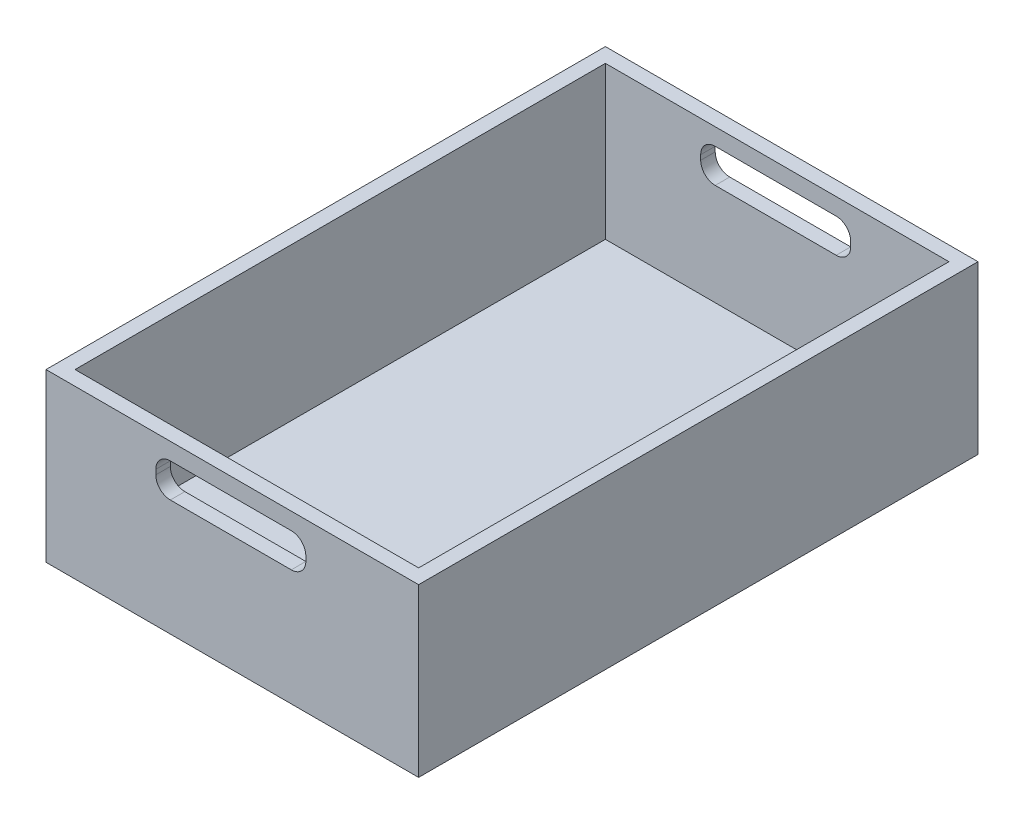
SolidWorks part; units mm, degrees
ref_plane "Front Plane" through (0, 0, 0) normal (0, 0, 1) x (1, 0, 0)
ref_plane "Top Plane" through (0, 0, 0) normal (0, 1, 0) x (1, 0, 0)
ref_plane "Right Plane" through (0, 0, 0) normal (1, 0, 0) x (0, 0, -1)
sketch "Sketch1" plane through (0, 0, 0) normal (0, 1, 0) x (1, 0, 0)
  line L1 (-192.5, -289) -> (192.5, -289)
  line L2 (-192.5, -289) -> (-192.5, 289)
  line L3 (-192.5, 289) -> (192.5, 289)
  line L4 (192.5, -289) -> (192.5, 289)
  line L5 (-192.5, -289) -> (192.5, 289) construction
  line L6 (-192.5, 289) -> (192.5, -289) construction
  point P0 (0, 0)
  dimension "D1" = 385
  dimension "D2" = 578
extrude "Boss-Extrude1" add sketch "Sketch1" along normal blind 15
sketch "Sketch2" plane through (0, 15, 0) normal (0, 1, 0) x (1, 0, 0)
  line L0 (192.5, 289) -> (-192.5, 289) construction
  line L1 (192.5, -289) -> (177.5, -289)
  line L2 (192.5, -289) -> (192.5, 289)
  line L3 (192.5, 289) -> (177.5, 289)
  line L4 (177.5, -289) -> (177.5, 289)
  dimension "D1" = 15
extrude "Boss-Extrude2" add sketch "Sketch2" along normal blind 157.5
mirror "Mirror1" about plane through (0, 0, 0) normal (1, 0, 0) of "Boss-Extrude2"
sketch "Sketch3" plane through (0, 15, 0) normal (0, 1, 0) x (1, 0, 0)
  line L0 (177.5, 289) -> (177.5, -289) construction
  line L1 (-177.5, -289) -> (177.5, -289)
  line L2 (-177.5, -289) -> (-177.5, -274)
  line L3 (-177.5, -274) -> (177.5, -274)
  line L4 (177.5, -289) -> (177.5, -274)
  dimension "D1" = 15
extrude "Boss-Extrude3" add sketch "Sketch3" along normal blind 157.5
mirror "Mirror2" about plane through (0, 0, 0) normal (0, 0, 1) of "Boss-Extrude3"
sketch "Sketch4" plane through (0, 0, 289) normal (0, 0, 1) x (1, 0, 0)
  line L1 (-64.0344, 155) -> (60.9656, 155)
  line L2 (-79.0344, 140) -> (-79.0344, 135)
  line L3 (-64.0344, 120) -> (60.9656, 120)
  line L4 (75.9656, 140) -> (75.9656, 135)
  line L5 (-79.0344, 155) -> (75.9656, 120) construction
  line L6 (-79.0344, 120) -> (75.9656, 155) construction
  line L7 (-192.5, 172.5) -> (192.5, 172.5) construction
  arc A0 (60.9656, 155) -> (75.9656, 140) centre (60.9656, 140) cw
  arc A1 (60.9656, 120) -> (75.9656, 135) centre (60.9656, 135) ccw
  arc A2 (-79.0344, 135) -> (-64.0344, 120) centre (-64.0344, 135) ccw
  arc A3 (-64.0344, 155) -> (-79.0344, 140) centre (-64.0344, 140) ccw
  point P0 (-1.5344, 137.5)
  dimension "D1" = 35
  dimension "D2" = 125
  dimension "D3" = 5
extrude "Cut-Extrude1" cut sketch "Sketch4" against normal through all both and the other way through all
